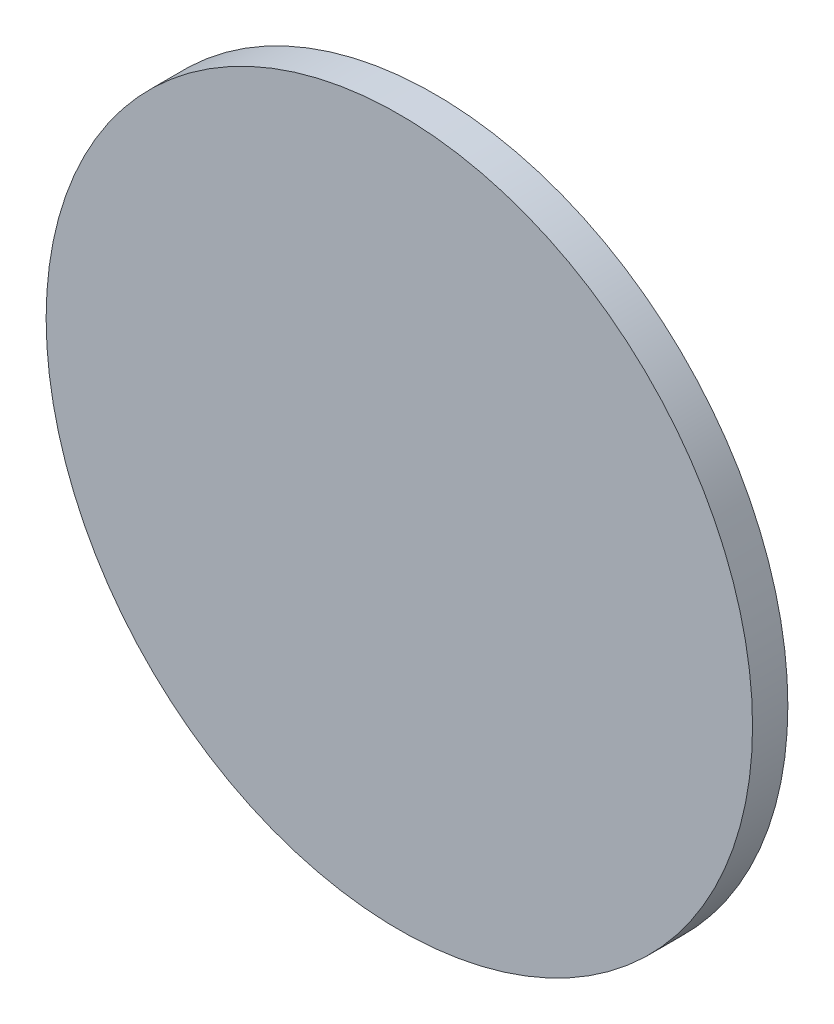
SolidWorks part; units mm, degrees
ref_plane "Front Plane" through (0, 0, 0) normal (0, 0, 1) x (1, 0, 0)
ref_plane "Top Plane" through (0, 0, 0) normal (0, 1, 0) x (1, 0, 0)
ref_plane "Right Plane" through (0, 0, 0) normal (1, 0, 0) x (0, 0, -1)
sketch "Sketch1" plane through (0, 0, 0) normal (0, 0, 1) x (1, 0, 0)
  circle A0 centre (0, 0) radius 100
extrude "Boss-Extrude1" add sketch "Sketch1" along normal blind 10
